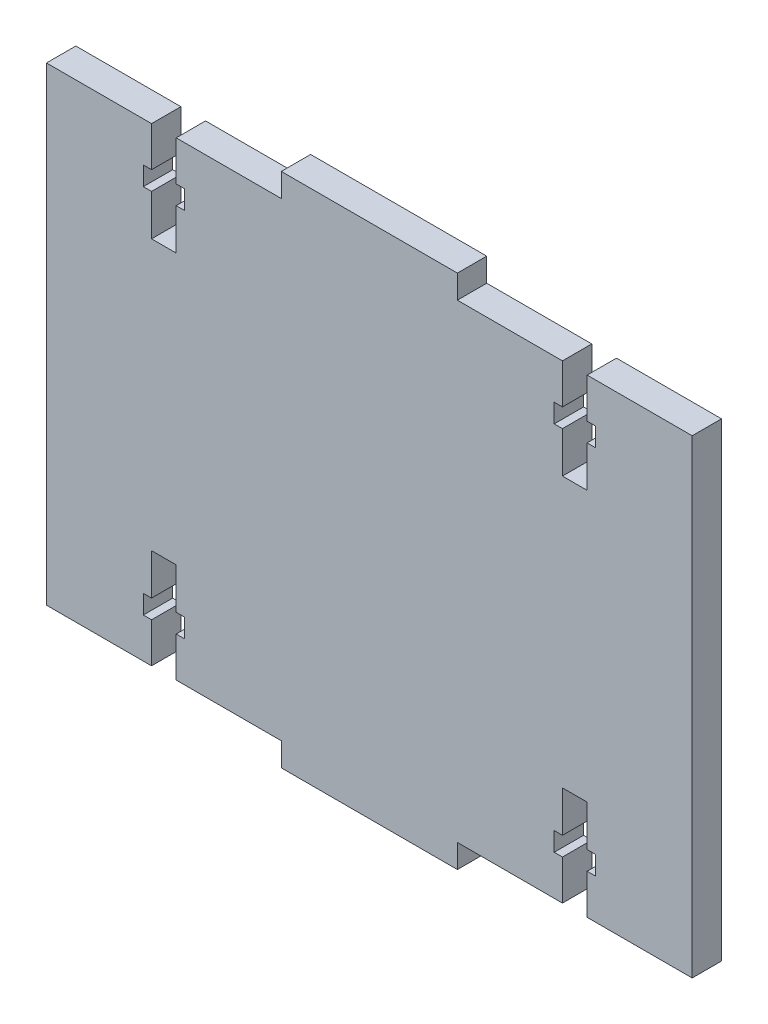
SolidWorks part; units mm, degrees
material "Balsa"
ref_plane "Plan de face" through (0, 0, 0) normal (0, 0, 1) x (1, 0, 0)
ref_plane "Plan de dessus" through (0, 0, 0) normal (0, 1, 0) x (1, 0, 0)
ref_plane "Plan de droite" through (0, 0, 0) normal (1, 0, 0) x (0, 0, -1)
sketch "Esquisse1" plane through (0, 0, 0) normal (0, 0, 1) x (1, 0, 0)
  line L1 (0, 0) -> (110, 0)
  line L2 (0, 0) -> (0, 80)
  line L3 (0, 80) -> (110, 80)
  line L4 (110, 0) -> (110, 80)
  dimension "D1" = 110
  dimension "D2" = 80
extrude "Boss.-Extru.1" add sketch "Esquisse1" along normal blind 5
sketch "Esquisse3" plane through (0, 0, 5) normal (0, 0, 1) x (1, 0, 0)
  line L0 (55, 80) -> (55, 0) construction
  line L1 (110, 80) -> (0, 80) construction
  line L2 (0, 0) -> (110, 0) construction
  line L3 (0, 40) -> (110, 40) construction
  line L4 (0, 80) -> (0, 0) construction
  line L5 (110, 0) -> (110, 80) construction
  line L6 (20, 80) -> (20, 63) construction
  line L7 (22.1, 80) -> (17.9, 80)
  line L8 (17.9, 80) -> (17.9, 73.2)
  line L9 (17.9, 73.2) -> (16.5, 73.2)
  line L10 (16.5, 73.2) -> (16.5, 70)
  line L11 (16.5, 70) -> (17.9, 70)
  line L12 (17.9, 70) -> (17.9, 63)
  line L13 (17.9, 63) -> (22.1, 63)
  line L14 (22.1, 70) -> (22.1, 63)
  line L15 (23.5, 70) -> (22.1, 70)
  line L16 (23.5, 73.2) -> (23.5, 70)
  line L17 (22.1, 73.2) -> (23.5, 73.2)
  line L18 (22.1, 80) -> (22.1, 73.2)
  line L19 (90, 80) -> (90, 63) construction
  line L20 (87.9, 80) -> (87.9, 73.2)
  line L21 (87.9, 73.2) -> (86.5, 73.2)
  line L22 (86.5, 73.2) -> (86.5, 70)
  line L23 (86.5, 70) -> (87.9, 70)
  line L24 (87.9, 70) -> (87.9, 63)
  line L25 (92.1, 63) -> (87.9, 63)
  line L26 (92.1, 70) -> (92.1, 63)
  line L27 (93.5, 70) -> (92.1, 70)
  line L28 (93.5, 73.2) -> (93.5, 70)
  line L29 (92.1, 73.2) -> (93.5, 73.2)
  line L30 (92.1, 80) -> (92.1, 73.2)
  line L31 (87.9, 80) -> (92.1, 80)
  line L32 (90, 0) -> (90, 17) construction
  line L33 (20, 0) -> (20, 17) construction
  line L34 (87.9, 0) -> (92.1, 0)
  line L35 (92.1, 0) -> (92.1, 6.8)
  line L36 (92.1, 6.8) -> (93.5, 6.8)
  line L37 (93.5, 6.8) -> (93.5, 10)
  line L38 (93.5, 10) -> (92.1, 10)
  line L39 (92.1, 10) -> (92.1, 17)
  line L40 (92.1, 17) -> (87.9, 17)
  line L41 (87.9, 10) -> (87.9, 17)
  line L42 (86.5, 10) -> (87.9, 10)
  line L43 (86.5, 6.8) -> (86.5, 10)
  line L44 (87.9, 6.8) -> (86.5, 6.8)
  line L45 (87.9, 0) -> (87.9, 6.8)
  line L46 (22.1, 0) -> (22.1, 6.8)
  line L47 (22.1, 6.8) -> (23.5, 6.8)
  line L48 (23.5, 6.8) -> (23.5, 10)
  line L49 (23.5, 10) -> (22.1, 10)
  line L50 (22.1, 10) -> (22.1, 17)
  line L51 (17.9, 17) -> (22.1, 17)
  line L52 (17.9, 10) -> (17.9, 17)
  line L53 (16.5, 10) -> (17.9, 10)
  line L54 (16.5, 6.8) -> (16.5, 10)
  line L55 (17.9, 6.8) -> (16.5, 6.8)
  line L56 (17.9, 0) -> (17.9, 6.8)
  line L57 (22.1, 0) -> (17.9, 0)
  point P26 (22.1, 76.6)
  point P27 (23.5, 71.6)
  dimension "D1" = 4.2
  dimension "D2" = 7
  dimension "D3" = 17
  dimension "D4" = 3.2
  dimension "D5" = 10
  dimension "D6" = 20
extrude "Enlèv. mat.-Extru.2" cut sketch "Esquisse3" against normal through all
sketch "Esquisse4" plane through (0, 0, 0) normal (0, 0, -1) x (-1, 0, 0)
  line L0 (-55, 0) -> (-55, 80) construction
  line L1 (-22.1, 0) -> (-87.9, 0) construction
  line L2 (-87.9, 80) -> (-22.1, 80) construction
  line L4 (-40, -4) -> (-70, -4)
  line L5 (-40, -4) -> (-40, 84)
  line L6 (-40, 84) -> (-70, 84)
  line L7 (-70, -4) -> (-70, 84)
  line L9 (-22.1, 17) -> (-17.9, 17) construction
  line L10 (-22.1, 0) -> (-87.9, 0) construction
  line L12 (-87.9, 80) -> (-22.1, 80) construction
  point P10 (-55, 84)
  point P17 (-20, 17)
  dimension "D1" = 20
  dimension "D2" = 4
  dimension "D3" = 4
extrude "Boss.-Extru.2" add sketch "Esquisse4" against normal blind 5
